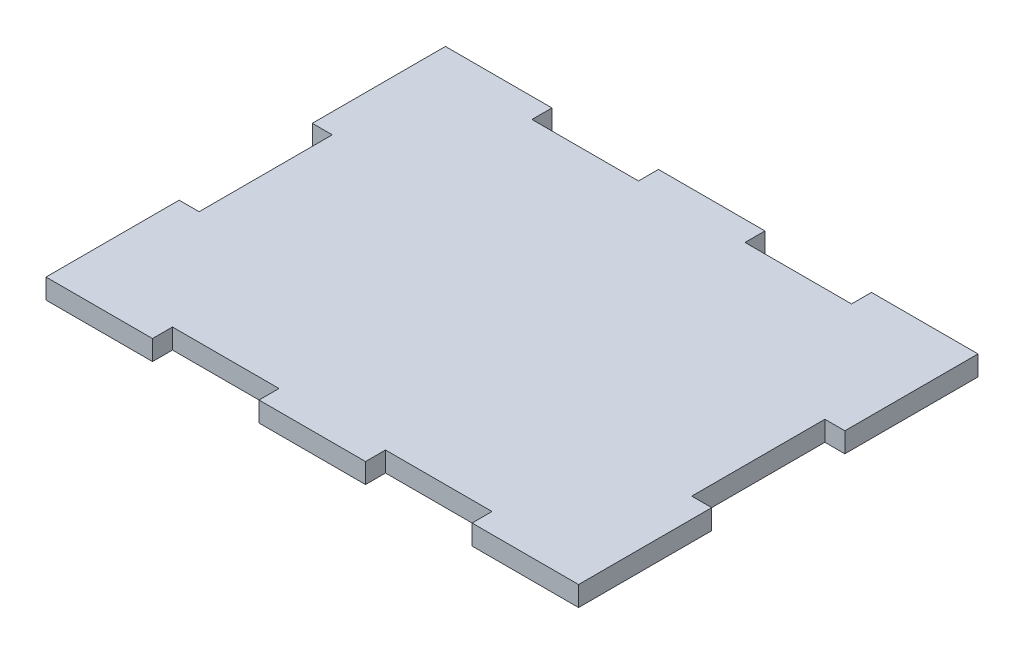
SolidWorks part; units mm, degrees
ref_plane "Front Plane" through (0, 0, 0) normal (0, 0, 1) x (1, 0, 0)
ref_plane "Top Plane" through (0, 0, 0) normal (0, 1, 0) x (1, 0, 0)
ref_plane "Right Plane" through (0, 0, 0) normal (1, 0, 0) x (0, 0, -1)
sketch "Top and Bottom" plane through (0, 0, 0) normal (0, 1, 0) x (1, 0, 0)
  line L0 (32, 60) -> (48, 60)
  line L1 (0, 0) -> (16, 0)
  line L2 (0, 0) -> (0, 20)
  line L3 (0, 60) -> (16, 60)
  line L4 (80, 0) -> (80, 20)
  line L5 (64, 60) -> (80, 60)
  line L6 (16, 60) -> (16, 57)
  line L7 (16, 57) -> (32, 57)
  line L8 (32, 60) -> (32, 57)
  line L10 (48, 60) -> (48, 57)
  line L11 (48, 57) -> (64, 57)
  line L12 (64, 60) -> (64, 57)
  line L14 (64, 0) -> (64, 3)
  line L15 (48, 3) -> (64, 3)
  line L16 (48, 0) -> (48, 3)
  line L17 (32, 0) -> (32, 3)
  line L18 (16, 0) -> (16, 3)
  line L19 (16, 3) -> (32, 3)
  line L20 (64, 0) -> (80, 0)
  line L21 (32, 0) -> (48, 0)
  line L22 (0, 40) -> (0, 60)
  line L23 (0, 40) -> (3, 40)
  line L24 (80, 40) -> (77, 40)
  line L25 (0, 20) -> (3, 20)
  line L26 (3, 40) -> (3, 20)
  line L27 (77, 40) -> (77, 20)
  line L28 (80, 20) -> (77, 20)
  line L29 (80, 40) -> (80, 60)
  dimension "D1" = 60
  dimension "D2" = 80
  dimension "D3" = 3
  dimension "D4" = 16
  dimension "D5" = 16
  dimension "D6" = 16
  dimension "D7" = 3
  dimension "D8" = 16
  dimension "D9" = 20
  dimension "D10" = 3
  dimension "D11" = 20
  dimension "D12" = 20
  dimension "D13" = 20
  dimension "D14" = 3
  dimension "D15" = 3
extrude "Top and Bottom Extruded" add sketch "Top and Bottom" along normal blind 3
